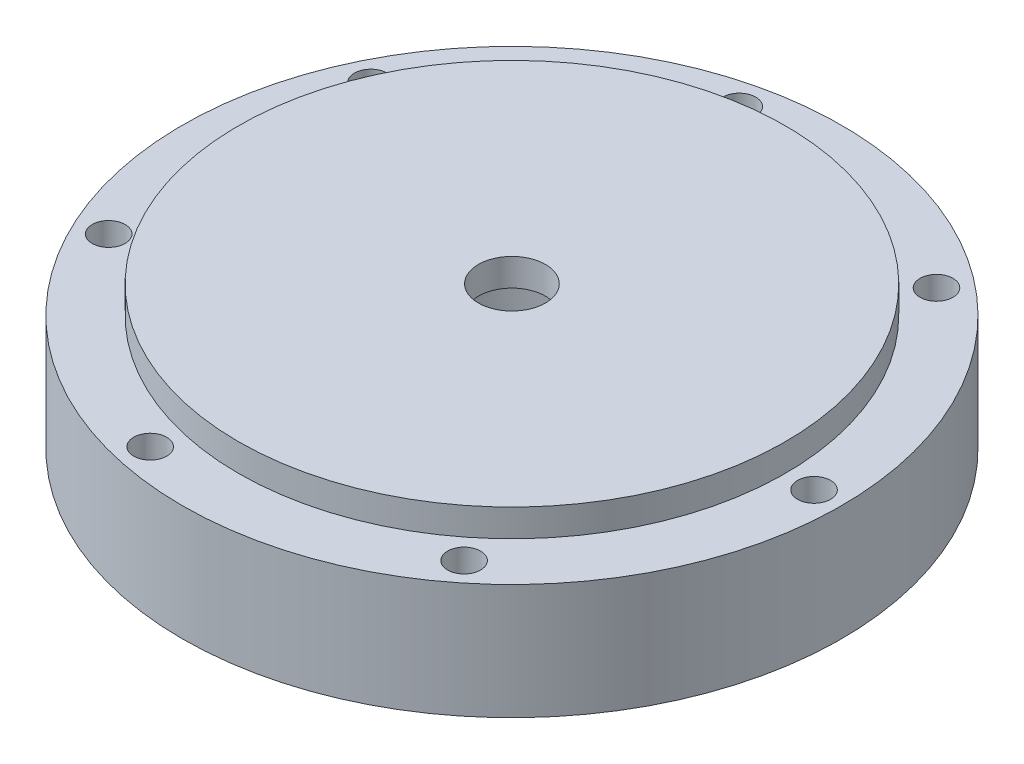
SolidWorks part; units mm, degrees
ref_plane "Alzado" through (0, 0, 0) normal (0, 0, 1) x (1, 0, 0)
ref_plane "Planta" through (0, 0, 0) normal (0, 1, 0) x (1, 0, 0)
ref_plane "Vista lateral" through (0, 0, 0) normal (1, 0, 0) x (0, 0, -1)
sketch "Croquis1" plane through (0, 0, 0) normal (0, 1, 0) x (1, 0, 0)
  circle A0 centre (0, 0) radius 24.9
  circle A1 centre (0, 0) radius 3.05
  dimension "D1" = 49.8
  dimension "D2" = 6.1
extrude "Saliente-Extruir1" add sketch "Croquis1" along normal blind 2.5
sketch "Croquis2" plane through (0, 0, 0) normal (0, 1, 0) x (1, 0, 0)
  line L0 (-4.1352, 9.05) -> (4.1352, 9.05)
  line L1 (-4.1352, -9.05) -> (4.1352, -9.05)
  circle A0 centre (0, 0) radius 30
  arc A1 (-4.5921, 8.9395) -> (-4.5921, -8.9395) centre (0, 0) ccw
  arc A2 (4.5921, -8.9395) -> (4.5921, 8.9395) centre (0, 0) ccw
  arc A3 (4.1352, -9.05) -> (4.5921, -8.9395) centre (4.1352, -8.05) ccw
  arc A4 (-4.1352, -9.05) -> (-4.5921, -8.9395) centre (-4.1352, -8.05) cw
  arc A5 (4.1352, 9.05) -> (4.5921, 8.9395) centre (4.1352, 8.05) cw
  arc A6 (-4.1352, 9.05) -> (-4.5921, 8.9395) centre (-4.1352, 8.05) ccw
  point P9 (4.3704, -9.05)
  dimension "D1" = 60
  dimension "D2" = 20.1
  dimension "D5" = 1
  dimension "D3" = 18.1
  dimension "D4" = 9.05
extrude "Saliente-Extruir2" add sketch "Croquis2" against normal blind 10.5
sketch "Croquis3" plane through (0, 0, 0) normal (0, 1, 0) x (1, 0, 0)
  circle A0 centre (27.5, 0) radius 1.5
  circle A1 centre (17.146, -21.5004) radius 1.5
  circle A2 centre (-6.1193, -26.8105) radius 1.5
  circle A3 centre (-24.7766, -11.9318) radius 1.5
  circle A4 centre (-24.7766, 11.9318) radius 1.5
  circle A5 centre (-6.1193, 26.8105) radius 1.5
  circle A6 centre (17.146, 21.5004) radius 1.5
  point P17 (0, 0)
  dimension "D2" = 3
  dimension "D1" = 27.5
  dimension "D3" = 7
extrude "Cortar-Extruir1" cut sketch "Croquis3" against normal through all
